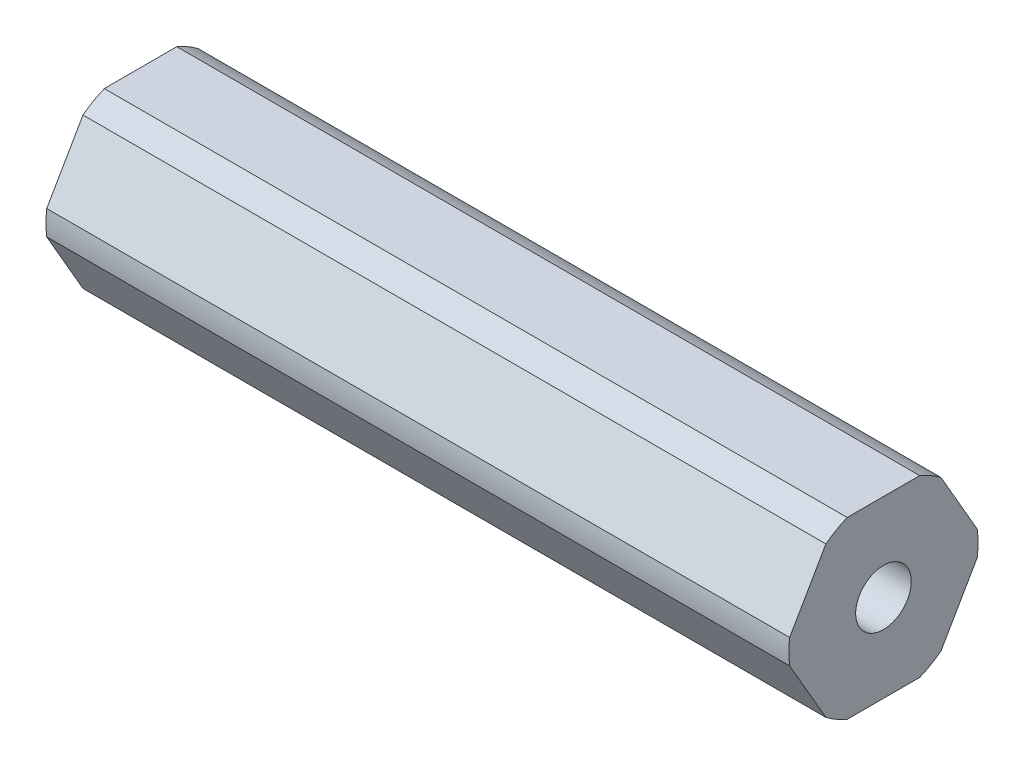
SolidWorks part; units mm, degrees
material "6061-T6 (SS)"
ref_plane "Front Plane" through (0, 0, 0) normal (0, 0, 1) x (1, 0, 0)
ref_plane "Top Plane" through (0, 0, 0) normal (0, 1, 0) x (1, 0, 0)
ref_plane "Right Plane" through (0, 0, 0) normal (1, 0, 0) x (0, 0, -1)
sketch "Sketch1" plane through (0, 0, 0) normal (1, 0, 0) x (0, 0, -1)
  line L1 (7.3323, 0) -> (3.6662, 6.35)
  line L2 (3.6662, 6.35) -> (-3.6662, 6.35)
  line L3 (-3.6662, 6.35) -> (-7.3323, 0)
  line L4 (-7.3323, 0) -> (-3.6662, -6.35)
  line L5 (-3.6662, -6.35) -> (3.6662, -6.35)
  line L6 (3.6662, -6.35) -> (7.3323, 0)
  circle A0 centre (0, 0) radius 6.35 construction
  circle A1 centre (0, 0) radius 6.875
  circle A2 centre (0, 0) radius 2.0193
  dimension "D1" = 12.7
  dimension "D2" = 13.75
  dimension "D3" = 4.0386
extrude "Boss-Extrude1" add sketch "Sketch1" along normal mid plane 53.975 contours L1 A1 L2 L3 L4 L5 L6 A2
equation "\"D2@Sketch1\"=13.75MM"
equation "\"D3@Sketch1\"=.159"
